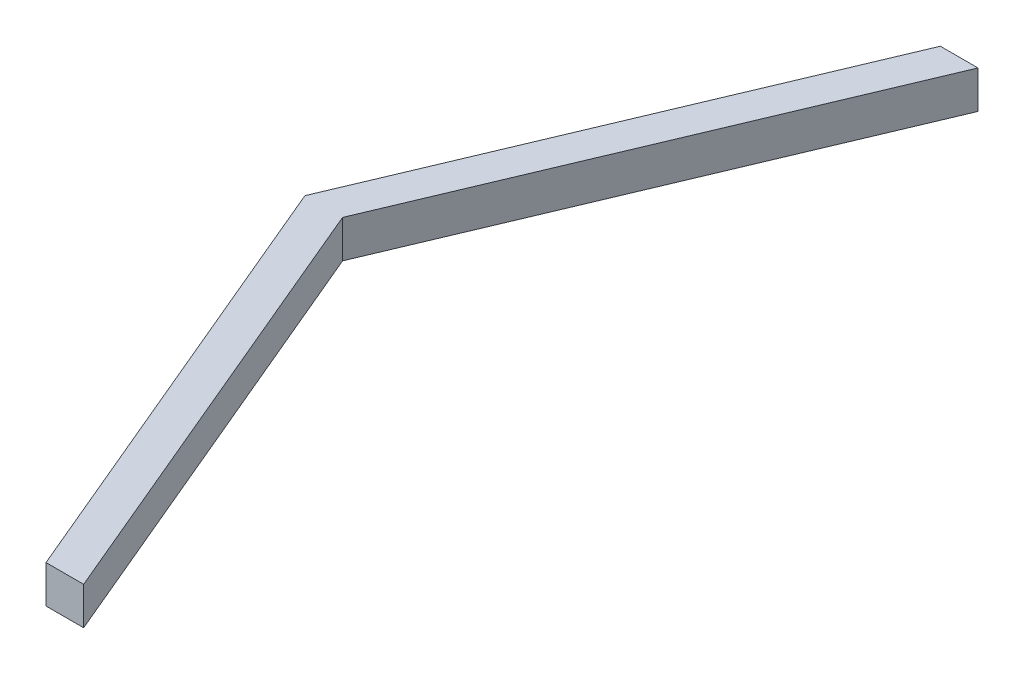
SolidWorks part; units mm, degrees
ref_plane "Front Plane" through (0, 0, 0) normal (0, 0, 1) x (1, 0, 0)
ref_plane "Top Plane" through (0, 0, 0) normal (0, 1, 0) x (1, 0, 0)
ref_plane "Right Plane" through (0, 0, 0) normal (1, 0, 0) x (0, 0, -1)
sketch "Sketch1" plane through (0, 0, 0) normal (0, 1, 0) x (1, 0, 0)
  line L0 (0, 301.625) -> (0, -301.625) construction
  line L1 (0, 301.625) -> (-25.4, 301.625)
  line L2 (-25.4, 301.625) -> (-152.4, 0)
  line L3 (-152.4, 0) -> (-25.4, -301.625)
  line L4 (-25.4, -301.625) -> (0, -301.625)
  line L5 (0, -301.625) -> (-127, 0)
  line L6 (-127, 0) -> (0, 301.625)
  line L7 (-193.3396, 0) -> (0, 0) construction
  point P7 (0, 0)
  dimension "D1" = 603.25
  dimension "D2" = 25.4
  dimension "D3" = 127
extrude "Boss-Extrude1" add sketch "Sketch1" along normal blind 25.4
